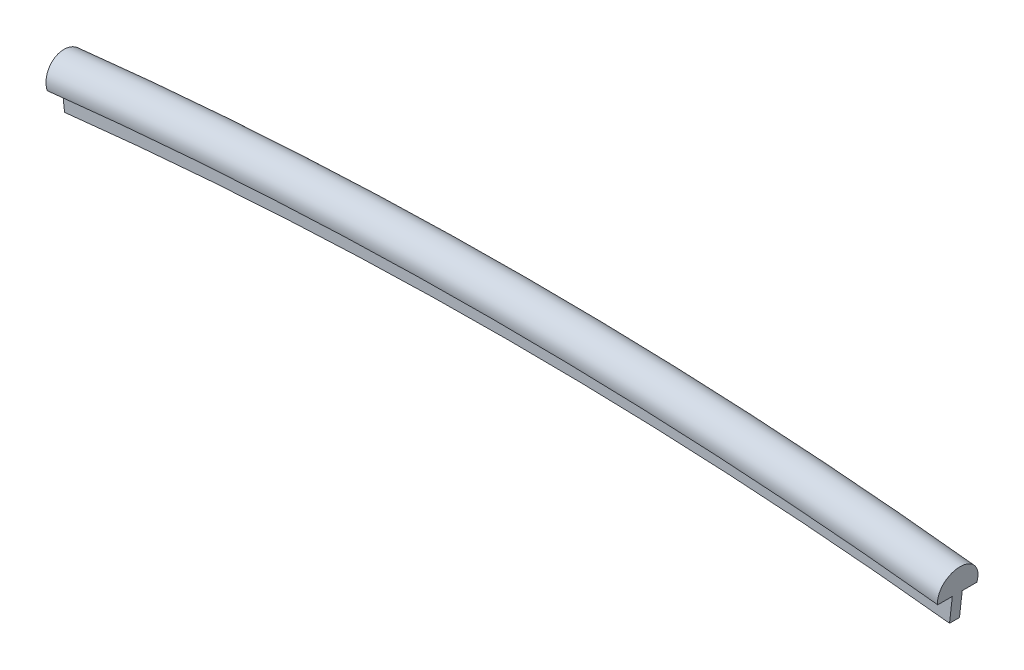
SolidWorks part; units mm, degrees
ref_plane "Front Plane" through (0, 0, 0) normal (0, 0, 1) x (1, 0, 0)
ref_plane "Top Plane" through (0, 0, 0) normal (0, 1, 0) x (1, 0, 0)
ref_plane "Right Plane" through (0, 0, 0) normal (1, 0, 0) x (0, 0, -1)
sketch "Sketch2" plane through (0, 0, 0) normal (1, 0, 0) x (0, 0, -1)
  line L0 (0, 241.3) -> (0, 0) construction
  line L2 (0, 241.3) -> (0, 239.8) construction
  line L3 (0, 239.8) -> (0.3, 239.8)
  line L4 (0, 239.8) -> (-0.3, 239.8)
  line L5 (-0.3, 239.8) -> (-0.3, 241.3)
  line L6 (0.3, 239.8) -> (0.3, 241.3)
  line L7 (0, 241.3) -> (0, 242.8) construction
  line L8 (-1.18, 241.3) -> (-0.3, 241.3)
  line L9 (0.3, 241.3) -> (1.18, 241.3)
  arc A0 (-1.18, 241.3) -> (1.18, 241.3) centre (0, 241.586) cw
  point P14 (0, 241.3)
ref_axis "Axis2" through (0, 0, 70.5976) along (0, 0, -1)
revolve "Revolve1" add sketch "Sketch2" angle 6.404 about axis through (0, 0, 70.5976) along (0, 0, -1)
